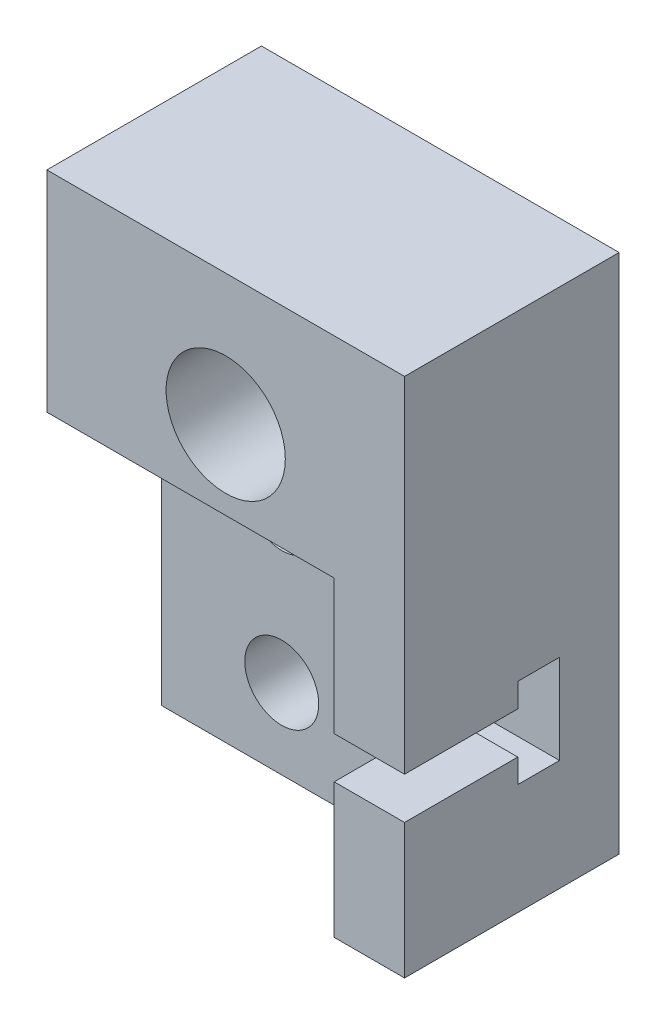
SolidWorks part; units mm, degrees
ref_plane "Front Plane" through (0, 0, 0) normal (0, 0, 1) x (1, 0, 0)
ref_plane "Top Plane" through (0, 0, 0) normal (0, 1, 0) x (1, 0, 0)
ref_plane "Right Plane" through (0, 0, 0) normal (1, 0, 0) x (0, 0, -1)
sketch "ProfileSketch3" plane through (0, 0, 0) normal (0, 0, 1) x (1, 0, 0)
  line L1 (0, 0) -> (15, 0)
  line L2 (0, 0) -> (0, 21.85)
  line L3 (0, 21.85) -> (15, 21.85)
  line L4 (15, 0) -> (15, 21.85)
  dimension "D6" = 15
  dimension "D1" = 21.85
extrude "ProfileBoss-Extrude1" add sketch "ProfileSketch3" along normal blind 9
sketch "MicroSwitchCutSketch4" plane through (0, 0, 9) normal (0, 0, 1) x (1, 0, 0)
  line L1 (0, 13.05) -> (12.05, 13.05)
  line L2 (0, 13.05) -> (0, 0)
  line L3 (0, 0) -> (12.05, 0)
  line L4 (12.05, 13.05) -> (12.05, 0)
  dimension "D1" = 12.05
  dimension "D2" = 13.05
extrude "MicroSwitchCut-Extrude1" cut sketch "MicroSwitchCutSketch4" against normal blind 4.8
sketch "Sketch5" plane through (0, 0, 4.2) normal (0, 0, 1) x (1, 0, 0)
  line L1 (0, 0) -> (12.05, 0) construction
  line L2 (12.05, 0) -> (12.05, 13.05) construction
  line L4 (12.05, 13.05) -> (0, 13.05) construction
  circle A0 centre (5.05, 9.7) radius 1.55
  circle A1 centre (5.05, 3.35) radius 1.55
  point P10 (11.05, 8.8)
  point P11 (0, 8.8)
  point P12 (15, 21.85)
  point P13 (11.05, 21.85)
  point P14 (15, 0)
  point P15 (15, 21.85)
  point P16 (0, 0)
  point P17 (15, 0)
  point P18 (0, 8.8)
  point P19 (0, 0)
  point P20 (-1, 8.8)
  point P21 (0, 8.8)
  point P22 (-1, 21.85)
  point P23 (-1, 8.8)
  point P24 (15, 21.85)
  point P25 (-1, 21.85)
  point P26 (15, 0)
  point P27 (15, 21.85)
  point P28 (0, 0)
  point P29 (15, 0)
  point P30 (0, 8.8)
  point P31 (0, 0)
  point P32 (11.05, 21.85)
  point P33 (-1, 21.85)
  point P34 (11.05, 8.8)
  point P35 (11.05, 21.85)
  point P36 (-1, 8.8)
  point P37 (0, 8.8)
  point P38 (0, 8.8)
  point P39 (11.05, 8.8)
  point P40 (-1, 21.85)
  point P41 (-1, 8.8)
  point P42 (11.05, 8.8)
  point P43 (11.05, 21.85)
  point P44 (0, 0)
  point P45 (15, 0)
  point P46 (0, 0)
  point P47 (0, 8.8)
  point P48 (-1, 21.85)
  point P49 (15, 21.85)
  point P50 (15, 0)
  point P51 (15, 21.85)
  point P52 (-1, 21.85)
  point P53 (-1, 8.8)
  point P54 (-1, 8.8)
  point P55 (0, 8.8)
  point P56 (-1, 21.85)
  point P57 (-1, 8.8)
  point P58 (-1, 21.85)
  point P59 (11.05, 21.85)
  point P60 (-1, 21.85)
  point P61 (-1, 8.8)
  point P62 (-1, 8.8)
  point P63 (11.05, 8.8)
  point P64 (11.05, 21.85)
  point P65 (11.05, 8.8)
  point P66 (2.75, 0)
  point P67 (-2.75, 0)
  point P68 (0, -2.75)
  point P69 (0, 2.75)
  dimension "D4" = 3.1
  dimension "D3" = 7
  dimension "D1" = 3.35
  dimension "D2" = 3.35
extrude "MicroSwitchMountingHolesCut-Extrude2" cut sketch "Sketch5" against normal blind 3.1
sketch "SmallChannelCableSketch6" plane through (0, 0, 9) normal (0, 0, 1) x (1, 0, 0)
  line L0 (12.05, 0) -> (12.05, 13.05) construction
  line L1 (12.05, 7.4) -> (15, 7.4)
  line L2 (12.05, 7.4) -> (12.05, 5.65)
  line L3 (12.05, 5.65) -> (15, 5.65)
  line L4 (15, 7.4) -> (15, 5.65)
  line L5 (15, 0) -> (15, 21.85) construction
  line L31 (12.05, 0) -> (15, 0) construction
  point P10 (1, 21.85)
  point P11 (1, 13.05)
  point P12 (16, 21.85)
  point P13 (1, 21.85)
  point P14 (16, 0)
  point P15 (16, 21.85)
  point P16 (12.05, 0)
  point P17 (16, 0)
  point P18 (1, 13.05)
  point P19 (0, 13.05)
  point P20 (1, 21.85)
  point P21 (1, 13.05)
  point P22 (16, 21.85)
  point P23 (1, 21.85)
  point P24 (16, 0)
  point P25 (16, 21.85)
  point P26 (0, 0)
  point P27 (16, 0)
  point P28 (0, 13.05)
  point P29 (0, 0)
  point P30 (12.05, 13.05)
  point P31 (1, 13.05)
  point P32 (1, 13.05)
  point P33 (0, 13.05)
  point P34 (12.05, 0)
  point P35 (12.05, 13.05)
  point P36 (0, 0)
  point P37 (12.05, 0)
  point P38 (0, 13.05)
  point P39 (0, 0)
  point P40 (12.05, 13.05)
  point P41 (1, 13.05)
  point P42 (12.05, 0)
  point P43 (12.05, 13.05)
  point P44 (5.05, 9.7)
  point P45 (6.5323, 10.1532)
  point P46 (5.05, 3.35)
  point P47 (6.5323, 3.8032)
  point P48 (5.05, 9.7)
  point P49 (6.5323, 10.1532)
  point P50 (5.05, 3.35)
  point P51 (6.5323, 3.8032)
  point P52 (0, 0)
  point P53 (16, 0)
  point P54 (0, 0)
  point P55 (0, 13.05)
  point P56 (1, 21.85)
  point P57 (16, 21.85)
  point P58 (16, 0)
  point P59 (16, 21.85)
  point P60 (1, 21.85)
  point P61 (1, 13.05)
  point P62 (1, 13.05)
  point P63 (0, 13.05)
  dimension "D1" = 1.75
  dimension "D2" = 5.65
extrude "SmallChannelCableCut-Extrude3" cut sketch "SmallChannelCableSketch6" against normal blind 4.75
sketch "LargeChannelCableSketch7" plane through (0, 0, 4.25) normal (0, 0, 1) x (1, 0, 0)
  line L0 (12.05, 7.4) -> (12.05, 13.05) construction
  line L1 (12.05, 8.4) -> (15, 8.4)
  line L2 (12.05, 8.4) -> (12.05, 4.65)
  line L3 (12.05, 4.65) -> (15, 4.65)
  line L4 (15, 8.4) -> (15, 4.65)
  line L5 (15, 0) -> (15, 5.65) construction
  line L6 (15, 7.4) -> (12.05, 7.4) construction
  dimension "D1" = 1
  dimension "D2" = 3.75
extrude "LargeChannelCableCut-Extrude4" cut sketch "LargeChannelCableSketch7" against normal blind 1.75
chamfer "Chamfer1" distance 1 angle 45 1 edges at (12.05, 6.525, 4.2)
sketch "Sketch6" plane through (0, 0, 9) normal (0, 0, 1) x (1, 0, 0)
  line L0 (0, 21.85) -> (0, 13.05) construction
  line L1 (15, 21.85) -> (0, 21.85) construction
  circle A0 centre (7.5, 16.35) radius 2.5
  dimension "D3" = 5
  dimension "D1" = 5.5
  dimension "D2" = 7.5
extrude "MicroSwitchMountingHoleCut-Extrude1" cut sketch "Sketch6" against normal through all
equation "\"SK8RodShaftSupportHeight\"= 42mm"
equation "\"SK8RodShaftSupportLength\"= 15mm"
equation "\"SK8MountHoleDiameter\"= 5mm"
equation "\"SK8RiserWidth\"= 6.75mm'Measured to meet Nema17 Mount Hole Center axis"
equation "\"SK8MountHoleFromSide\"= \"SK8RodShaftSupportLength\" / 2"
equation "\"SK8MountHoleFromEitherEnd\"= 5.5mm"
equation "\"MicroSwitchCutOutLength\"= 13.05mm"
equation "\"MicroSwitchHeight\"= 6.55mm"
equation "\"MicroSwitchMountingHoleOffsetFromSide\"= 3.35mm"
equation "\"MicroSwitchTerminalHeight\"= 3.5mm"
equation "\"MicroSwitchExtraMountingHeight\"= 2mm"
equation "\"MicroSwitchDepth\"= 2.8mm"
equation "\"MicroSwitchMountingHoleOffsetFromBottom\"= 7mm"
equation "\"M2HeatInsertHoleDiameter\"= 3mm + .1mm'Add .1mm for printing"
equation "\"M2HeatInsertHoleDepth\"= 3.1mm'Spec"
equation "\"D1@ProfileBoss-Extrude1\" = \"SK8RiserWidth\""
equation "\"D1@MicroSwitchCutSketch4\"=\"MicroSwitchCutOutHeight\""
equation "\"D2@MicroSwitchCutSketch4\" = \"MicroSwitchCutOutLength\""
equation "\"D1@MicroSwitchCut-Extrude1\"=\"MicroSwitchDepth\" + 2mm"
equation "\"D3@Sketch5\"=\"MicroSwitchMountingHoleOffsetFromBottom\""
equation "\"D4@Sketch5\"=\"M2HeatInsertHoleDiameter\""
equation "\"D1@MicroSwitchMountingHolesCut-Extrude2\" = \"M2HeatInsertHoleDepth\""
equation "\"MicroSwitchCutOutHeight\"= \"MicroSwitchExtraMountingHeight\" + \"MicroSwitchTerminalHeight\" + \"MicroSwitchHeight\""
equation "\"EndStopCableWidth\"= 3.75mm"
equation "\"D1@SmallChannelCableSketch6\" = \"EndStopCableDepth\""
equation "\"EndStopCableDepth\"= 1.75mm"
equation "\"D1@SmallChannelCableCut-Extrude3\"=\"EndStopCableDepth\" + 3mm"
equation "\"D1@LargeChannelCableSketch7\" =  ( \"EndStopCableWidth\" - \"EndStopCableDepth\" )  / 2"
equation "\"D2@LargeChannelCableSketch7\" = \"EndStopCableWidth\""
equation "\"D1@LargeChannelCableCut-Extrude4\" = \"EndStopCableDepth\""
equation "\"D6@ProfileSketch3\" = \"SK8RodShaftSupportLength\""
equation "\"D1@Sketch5\"=\"MicroSwitchMountingHoleOffsetFromSide\""
equation "\"D2@Sketch5\"=\"MicroSwitchMountingHoleOffsetFromSide\""
equation "\"D2@SmallChannelCableSketch6\"=(\"MicroSwitchCutOutLength\" - \"EndStopCableDepth\")/2"
equation "\"D1@Sketch6\"=\"SK8MountHoleFromEitherEnd\""
equation "\"D1@ProfileSketch3\" = \"MicroSwitchCutOutLength\" + \"SK8MountHoleFromEitherEnd\" * 1.6"
equation "\"D2@Sketch6\"=\"SK8RodShaftSupportLength\"/2"
